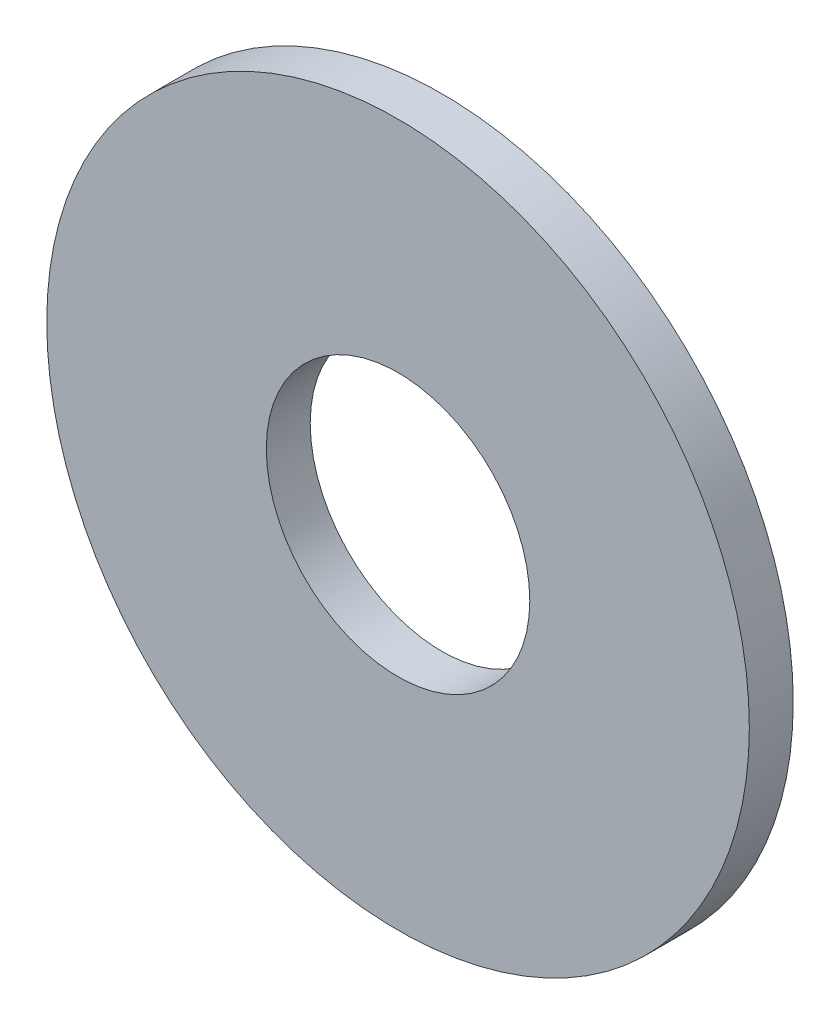
SolidWorks part; units mm, degrees
material "PE High Density"
ref_plane "Front" through (0, 0, 0) normal (0, 0, 1) x (1, 0, 0)
ref_plane "Top" through (0, 0, 0) normal (0, 1, 0) x (1, 0, 0)
ref_plane "Right" through (0, 0, 0) normal (1, 0, 0) x (0, 0, -1)
sketch "Sketch1" plane through (0, 0, 0) normal (0, 0, 1) x (1, 0, 0)
  circle A0 centre (0, 0) radius 8
extrude "Boss-Extrude1" add sketch "Sketch1" along normal blind 10
sketch "Sketch2" plane through (0, 0, 0) normal (0, 0, -1) x (-1, 0, 0)
  circle A0 centre (0, 0) radius 8
extrude "Cut-Extrude1" cut sketch "Sketch2" against normal blind 9
sketch "Sketch3" plane through (0, 0, 9) normal (0, 0, -1) x (-1, 0, 0)
  circle A0 centre (0, 0) radius 3
extrude "Cut-Extrude2" cut sketch "Sketch3" against normal blind 9
